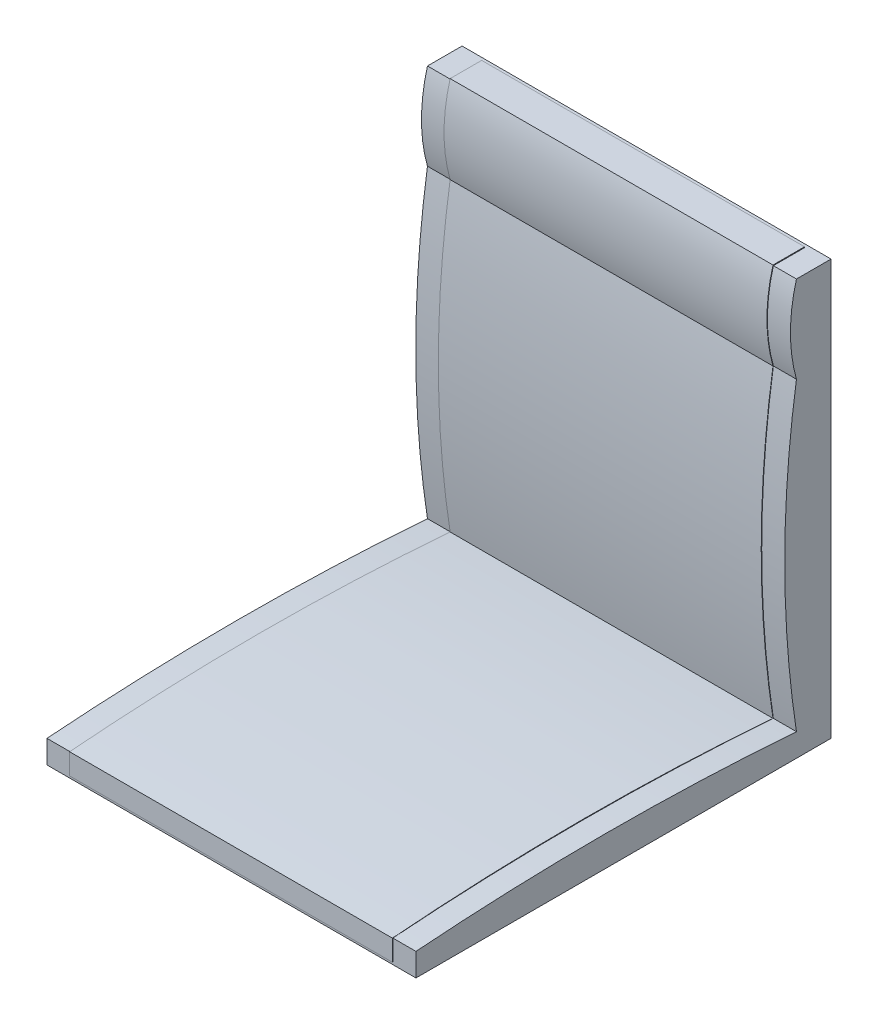
SolidWorks part; units mm, degrees
ref_plane "Front Plane" through (0, 0, 0) normal (0, 0, 1) x (1, 0, 0)
ref_plane "Top Plane" through (0, 0, 0) normal (0, 1, 0) x (1, 0, 0)
ref_plane "Right Plane" through (0, 0, 0) normal (1, 0, 0) x (0, 0, -1)
sketch "Sketch2" plane through (0, 0, 0) normal (0, 1, 0) x (1, 0, 0)
  line L1 (-203.2, -228.6) -> (203.2, -228.6)
  line L2 (-203.2, -228.6) -> (-203.2, 228.6)
  line L3 (-203.2, 228.6) -> (203.2, 228.6)
  line L4 (203.2, -228.6) -> (203.2, 228.6)
  line L5 (-203.2, -228.6) -> (203.2, 228.6) construction
  line L6 (-203.2, 228.6) -> (203.2, -228.6) construction
  point P0 (0, 0)
extrude "Boss-Extrude1" add sketch "Sketch2" along normal blind 25.4 from offset 406.4
sketch "Sketch4" plane through (0, 431.8, 0) normal (0, 1, 0) x (1, 0, 0)
sketch "Sketch5" plane through (0, 431.8, 0) normal (0, 1, 0) x (1, 0, 0)
  line L0 (203.2, 228.6) -> (-203.2, 228.6) construction
  line L1 (-203.2, 228.6) -> (203.2, 228.6)
  line L2 (-203.2, 228.6) -> (-203.2, 190.5)
  line L3 (-203.2, 190.5) -> (203.2, 190.5)
  line L4 (203.2, 228.6) -> (203.2, 190.5)
  line L5 (-203.2, 228.6) -> (-203.2, -228.6) construction
  line L6 (203.2, -228.6) -> (203.2, 228.6) construction
extrude "Boss-Extrude2" add sketch "Sketch5" along normal blind 431.8
sketch "Sketch6" plane through (203.2, 0, 0) normal (1, 0, 0) x (0, 0, -1)
  line L0 (190.5, 863.6) -> (228.6, 863.6) construction
  line L1 (190.5, 431.8) -> (228.6, 431.8)
  line L2 (228.6, 863.6) -> (228.6, 406.4) construction
  line L3 (228.6, 431.8) -> (228.6, 863.6)
  line L4 (228.6, 863.6) -> (209.55, 863.6)
  arc A0 (209.55, 863.6) -> (190.5, 431.8) centre (1283.6488, 599.8931) ccw
extrude "Boss-Extrude3" add sketch "Sketch6" against normal blind 406.4
sketch "Sketch7" plane through (203.2, 0, 0) normal (1, 0, 0) x (0, 0, -1)
  line L0 (-228.6, 431.8) -> (-228.6, 406.4)
  line L1 (-228.6, 406.4) -> (190.5, 406.4)
  line L2 (-228.6, 406.4) -> (228.6, 406.4) construction
  line L3 (190.5, 406.4) -> (190.5, 431.8)
  arc A0 (-228.6, 431.8) -> (190.5, 431.8) centre (-19.05, -2322.3885) cw
extrude "Boss-Extrude5" add sketch "Sketch7" against normal blind 406.4
sketch "Sketch8" plane through (203.2, 0, 0) normal (1, 0, 0) x (0, 0, -1)
  line L0 (190.5, 863.6) -> (228.6, 863.6)
  line L1 (228.6, 863.6) -> (228.6, 767.9861)
  line L2 (228.6, 863.6) -> (228.6, 406.4) construction
  line L3 (228.6, 767.9861) -> (190.5, 767.9861)
  arc A0 (190.5, 767.9861) -> (190.5, 863.6) centre (360.2313, 815.7931) cw
extrude "Boss-Extrude6" add sketch "Sketch8" against normal blind 406.4
sketch "Sketch9" plane through (203.2, 0, 0) normal (1, 0, 0) x (0, 0, -1)
  line L0 (190.0645, 864.4839) -> (224.7932, 864.4839)
  line L1 (224.7932, 864.4839) -> (224.7932, 863.6)
  line L8 (190.5, 863.6) -> (224.7932, 863.6)
  line L9 (190.5, 863.6) -> (228.6, 863.6) construction
  line L10 (224.7932, 863.6) -> (224.7932, 408.9765)
  line L11 (224.7932, 408.9765) -> (-229.126, 408.9765)
  line L12 (-229.126, 408.9765) -> (-229.126, 432.0051)
  arc A0 (190.0645, 432.0051) -> (190.0645, 768.108) centre (1271.9204, 600.0565) cw
  arc A1 (190.0645, 768.108) -> (190.0645, 864.4839) centre (360.2397, 816.2959) cw
  arc A6 (-229.126, 432.0051) -> (190.0645, 432.0051) centre (-19.5307, -2169.097) cw
extrude "Boss-Extrude8" add sketch "Sketch9" against normal blind 355.6 from offset 25.4 contours L10 L11 L12 A6 A0 A1 L0 L1 offset against normal yes
sketch "Sketch11" plane through (0, 406.4, 0) normal (0, -1, 0) x (1, 0, 0)
  line L0 (0, 0) -> (0, 1.932)
  line L1 (0, 1.932) -> (-1.331, 0)
  line L2 (-1.331, 0) -> (0, 0)
extrude "Boss-Extrude10" add sketch "Sketch11" along normal blind 12.7
